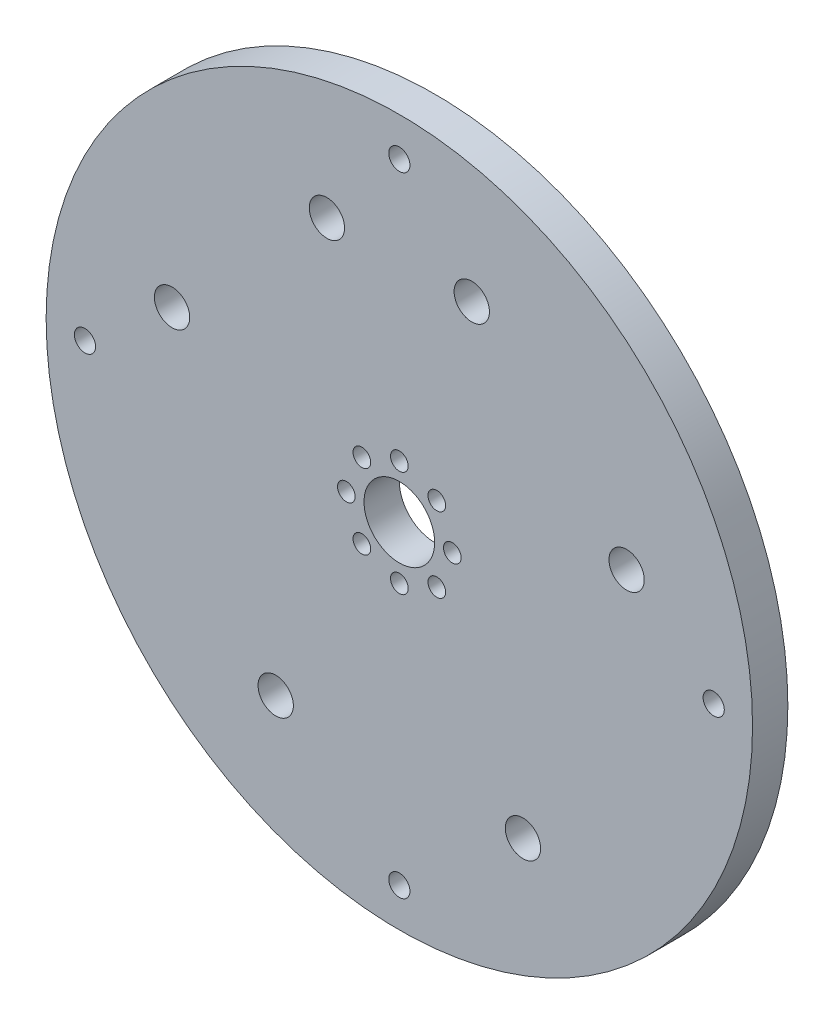
SolidWorks part; units mm, degrees
ref_plane "前视基准面" through (0, 0, 0) normal (0, 0, 1) x (1, 0, 0)
ref_plane "上视基准面" through (0, 0, 0) normal (0, 1, 0) x (1, 0, 0)
ref_plane "右视基准面" through (0, 0, 0) normal (1, 0, 0) x (0, 0, -1)
sketch "草图1" plane through (0, 0, 0) normal (0, 0, 1) x (1, 0, 0)
  line L0 (0, 30) -> (0, -30) construction
  line L1 (-21.2132, 21.2132) -> (-32.1734, 10.253) construction
  line L2 (-21.2132, 21.2132) -> (-10.253, 32.1734) construction
  circle A0 centre (0, 0) radius 50
  circle A1 centre (0, 0) radius 44.5 construction
  circle A2 centre (0, 44.5) radius 1.5
  circle A3 centre (44.5, 0) radius 1.5
  circle A4 centre (0, -44.5) radius 1.5
  circle A5 centre (-44.5, 0) radius 1.5
  circle A6 centre (0, 0) radius 7.5 construction
  circle A7 centre (0, 7.5) radius 1.25
  circle A8 centre (5.3033, 5.3033) radius 1.25
  circle A9 centre (7.5, 0) radius 1.25
  circle A10 centre (5.3033, -5.3033) radius 1.25
  circle A11 centre (0, -7.5) radius 1.25
  circle A12 centre (-5.3033, -5.3033) radius 1.25
  circle A13 centre (-7.5, 0) radius 1.25
  circle A14 centre (-5.3033, 5.3033) radius 1.25
  circle A15 centre (0, 0) radius 5
  circle A16 centre (0, 0) radius 30 construction
  circle A17 centre (-10.253, 32.1734) radius 2.5
  circle A18 centre (-32.1734, 10.253) radius 2.5
  circle A19 centre (10.253, 32.1734) radius 2.5
  circle A20 centre (32.1734, 10.253) radius 2.5
  circle A21 centre (-17.5, -30) radius 2.5
  circle A22 centre (17.5, -30) radius 2.5
  point P15 (0, 0)
  point P32 (0, 0)
  dimension "D1" = 100
  dimension "D2" = 89
  dimension "D3" = 3
  dimension "D5" = 15
  dimension "D6" = 2.5
  dimension "D8" = 10
  dimension "D9" = 60
  dimension "D12" = 5
  dimension "D13" = 5
  dimension "D16" = 5
  dimension "D17" = 5
  dimension "D10" = 15.5
  dimension "D11" = 15.5
  dimension "D14" = 17.5
  dimension "D15" = 17.5
  dimension "D4" = 4
  dimension "D7" = 8
extrude "凸台-拉伸1" add sketch "草图1" along normal blind 5
